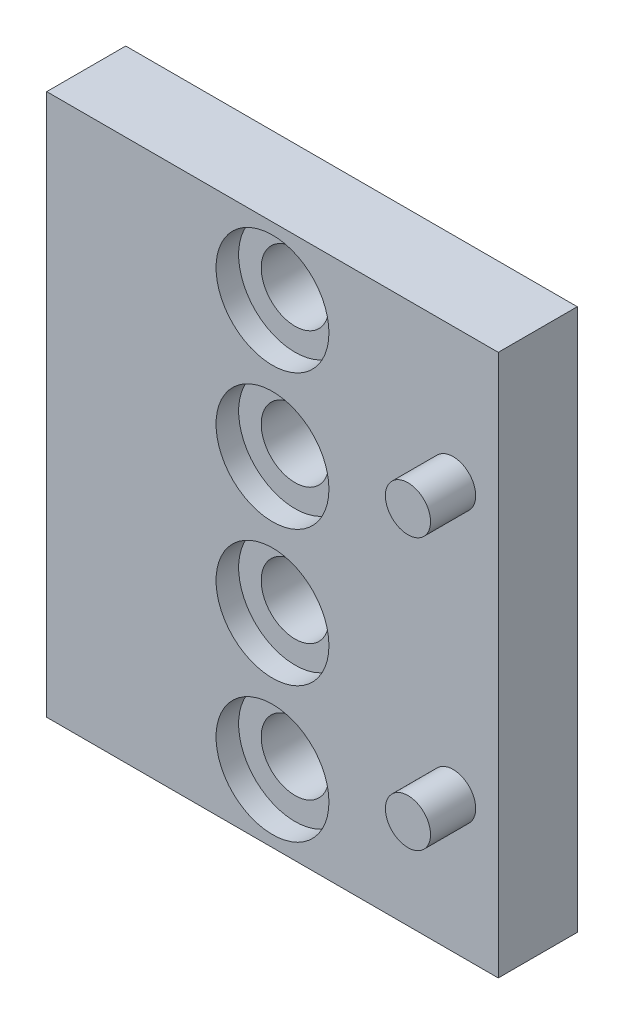
SolidWorks part; units mm, degrees
ref_plane "Front Plane" through (0, 0, 0) normal (0, 0, 1) x (1, 0, 0)
ref_plane "Top Plane" through (0, 0, 0) normal (0, 1, 0) x (1, 0, 0)
ref_plane "Right Plane" through (0, 0, 0) normal (1, 0, 0) x (0, 0, -1)
sketch "Sketch1" plane through (0, 0, 0) normal (0, 0, 1) x (1, 0, 0)
  line L1 (-10, 12) -> (10, 12)
  line L2 (-10, 12) -> (-10, -12)
  line L3 (-10, -12) -> (10, -12)
  line L4 (10, 12) -> (10, -12)
  point P4 (0, 12)
  point P6 (10, 0)
  dimension "D1" = 20
  dimension "D2" = 24
extrude "Boss-Extrude1" add sketch "Sketch1" along normal blind 3.5
sketch "Sketch2" plane through (0, 0, 0) normal (0, 0, -1) x (-1, 0, 0)
  line L1 (-8, 11) -> (8, 11)
  line L2 (-8, 11) -> (-8, -11)
  line L3 (-8, -11) -> (8, -11)
  line L4 (8, 11) -> (8, -11)
  point P4 (0, 11)
  point P6 (8, 0)
  dimension "D1" = 16
  dimension "D2" = 22
extrude "Cut-Extrude1" cut sketch "Sketch2" against normal blind 0.4
sketch "Sketch3" plane through (0, 0, 3.5) normal (0, 0, 1) x (1, 0, 0)
  line L0 (1.925, 0) -> (-1.925, 0) construction
  circle A0 centre (0, 3) radius 1.5
  circle A1 centre (0, 9) radius 1.5
  circle A2 centre (0, -9) radius 1.5
  circle A3 centre (0, -3) radius 1.5
  point P4 (0, 8.232)
  point P6 (0, 6.9668)
  point P7 (0, 0)
  point P8 (0, 0)
  dimension "D1" = 3
  dimension "D2" = 3
  dimension "D3" = 9
extrude "Cut-Extrude2" cut sketch "Sketch3" against normal through all
sketch "Sketch4" plane through (0, 0, 3.5) normal (0, 0, 1) x (1, 0, 0)
  circle A0 centre (0, 9) radius 2.5
  point P3 (0, 3)
  point P4 (0, -3)
  point P6 (0, -9)
  dimension "D1" = 5
extrude "Cut-Extrude3" cut sketch "Sketch4" against normal blind 1
pattern_sketch "Sketch-Pattern1" of "Cut-Extrude3" driven by "Sketch4"
sketch "Sketch5" plane through (0, 0, 3.5) normal (0, 0, 1) x (1, 0, 0)
  line L0 (1.925, 0) -> (-1.925, 0) construction
  circle A0 centre (8, 6) radius 1
  circle A2 centre (8, -6) radius 1
  point P5 (0, 0)
  point P6 (8.0393, 7.4945)
  dimension "D1" = 2
  dimension "D2" = 8
  dimension "D3" = 6
extrude "Boss-Extrude2" add sketch "Sketch5" along normal blind 2
